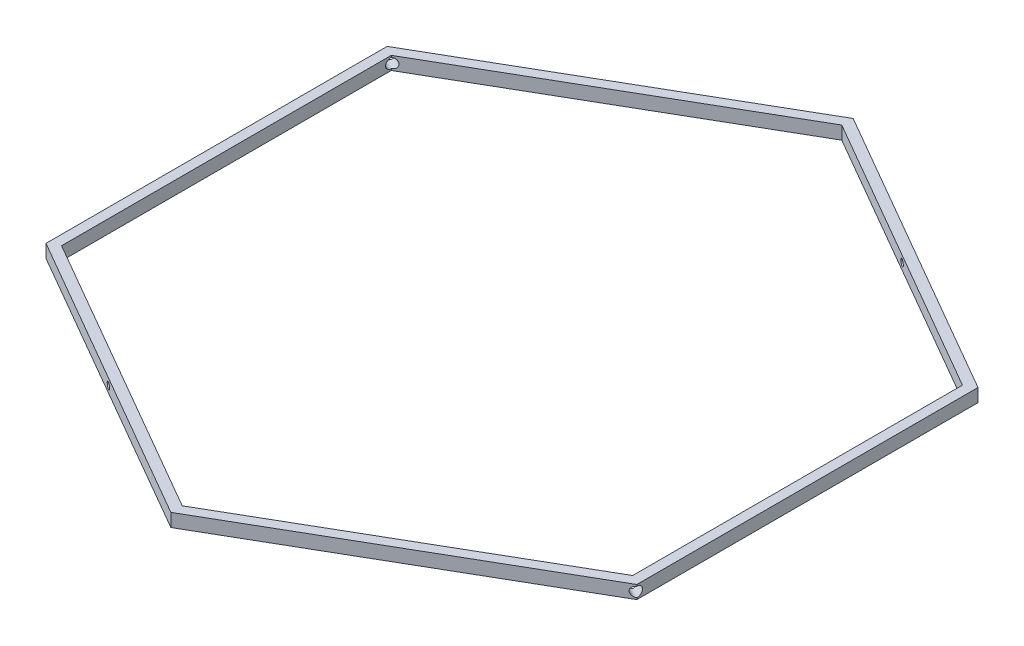
SolidWorks part; units mm, degrees
ref_plane "Plano frontal" through (0, 0, 0) normal (0, 0, 1) x (1, 0, 0)
ref_plane "Plano superior" through (0, 0, 0) normal (0, 1, 0) x (1, 0, 0)
ref_plane "Plano direito" through (0, 0, 0) normal (1, 0, 0) x (0, 0, -1)
sketch "Esboço1" plane through (0, 0, 0) normal (0, 1, 0) x (1, 0, 0)
  line L0 (90, -51.9615) -> (90, 51.9615)
  line L1 (90, 51.9615) -> (0, 103.923)
  line L2 (0, 103.923) -> (-90, 51.9615)
  line L3 (-90, 51.9615) -> (-90, -51.9615)
  line L4 (-90, -51.9615) -> (0, -103.923)
  line L5 (0, -103.923) -> (90, -51.9615)
  line L6 (87, 50.2295) -> (0, 100.4589)
  line L7 (0, 100.4589) -> (-87, 50.2295)
  line L8 (-87, 50.2295) -> (-87, -50.2295)
  line L9 (-87, -50.2295) -> (0, -100.4589)
  line L10 (0, -100.4589) -> (87, -50.2295)
  line L11 (87, -50.2295) -> (87, 50.2295)
  circle A0 centre (0, 0) radius 90 construction
  dimension "D1" = 180
  dimension "D2" = 3
extrude "Ressalto-extrusão1" add sketch "Esboço1" along normal blind 4
sketch "Esboço2" plane through (-45, 0, 77.9423) normal (-0.5, 0, 0.866) x (0.866, 0, 0.5)
  line L0 (-51.9615, 2) -> (0, 2) construction
  line L1 (-51.9615, 4) -> (-51.9615, 0) construction
  line L2 (0, 2) -> (51.9615, 2) construction
  line L3 (51.9615, 4) -> (51.9615, 0) construction
  circle A0 centre (0, 2) radius 1
  dimension "D1" = 2
extrude "Corte-extrusão1" cut sketch "Esboço2" against normal through all
ref_plane "Plano1" through (-43.5, 0, -25.1147) normal (-0.866, 0, -0.5) x (-0.5, 0, 0.866)
sketch "Esboço3" plane through (-43.5, 0, -25.1147) normal (-0.866, 0, -0.5) x (-0.5, 0, 0.866)
  line L0 (0, 4) -> (0, 0) construction
  circle A0 centre (0, 2) radius 1.5
  dimension "D1" = 3
extrude "Corte-extrusão2" cut sketch "Esboço3" against normal through all both and the other way through all
